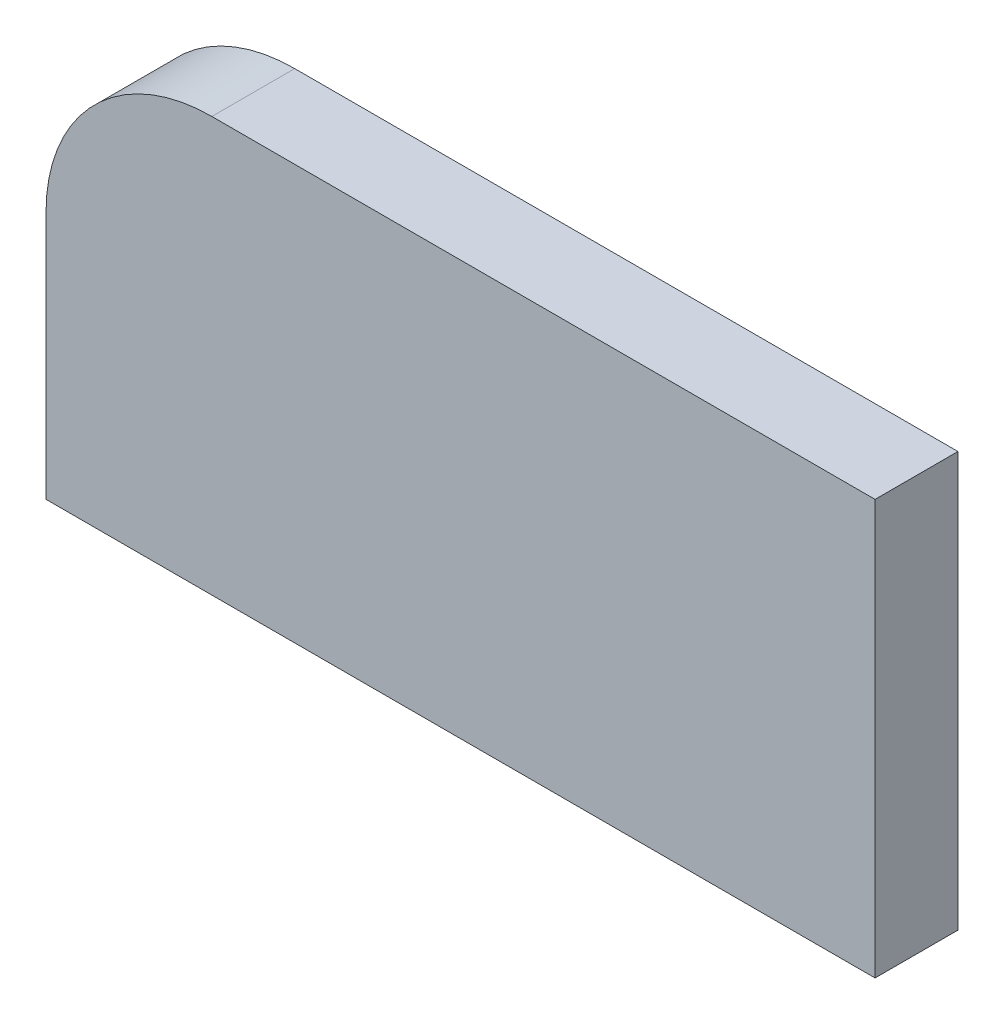
SolidWorks part; units mm, degrees
ref_plane "Plan de face" through (0, 0, 0) normal (0, 0, 1) x (1, 0, 0)
ref_plane "Plan de dessus" through (0, 0, 0) normal (0, 1, 0) x (1, 0, 0)
ref_plane "Plan de droite" through (0, 0, 0) normal (1, 0, 0) x (0, 0, -1)
sketch "Esquisse1" plane through (0, 0, 0) normal (0, 0, 1) x (1, 0, 0)
  line L0 (29, 12.5) -> (-11, 12.5)
  line L1 (29, 12.5) -> (29, -12.5)
  line L2 (29, -12.5) -> (-21, -12.5)
  line L3 (-21, 2.5) -> (-21, -12.5)
  arc A0 (-21, 2.5) -> (-11, 12.5) centre (-11, 2.5) cw
  dimension "D1" = 50
  dimension "D2" = 25
extrude "Extrusion1" add sketch "Esquisse1" along normal blind 5
